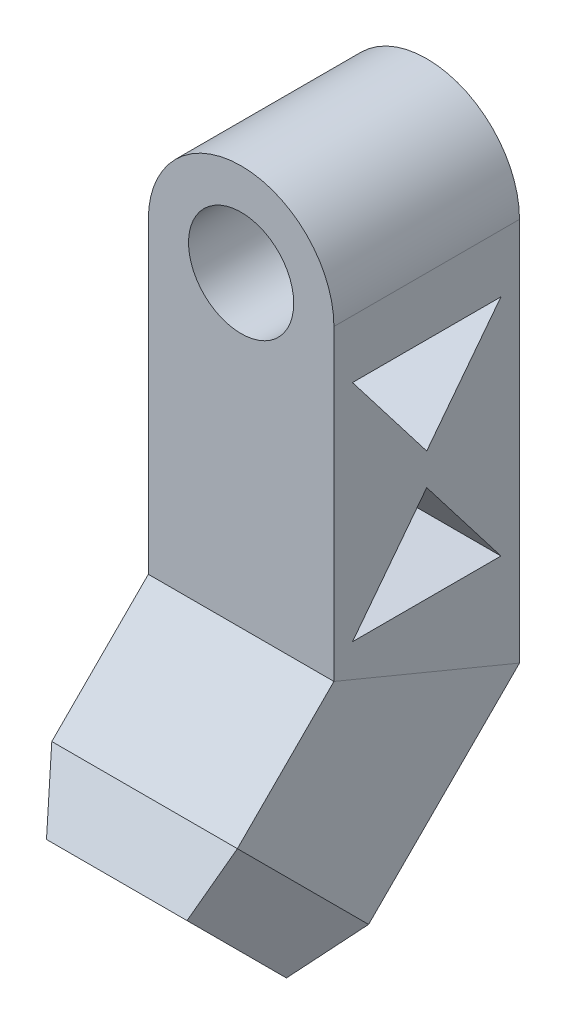
SolidWorks part; units mm, degrees
ref_plane "Front Plane" through (0, 0, 0) normal (0, 0, 1) x (1, 0, 0)
ref_plane "Top Plane" through (0, 0, 0) normal (0, 1, 0) x (1, 0, 0)
ref_plane "Right Plane" through (0, 0, 0) normal (1, 0, 0) x (0, 0, -1)
ref_plane "Plane2" through (0, 96.393, 0) normal (0, 1, 0) x (1, 0, 0)
sketch "Sketch10" plane through (0, 0, 0) normal (1, 0, 0) x (0, 0, -1)
  line L0 (0, 96.393) -> (0, 25.4)
  line L1 (55, 96.393) -> (-55, 96.393) construction
  line L2 (0, 25.4) -> (-25.4, 0)
  line L3 (55, 0) -> (-55, 0) construction
  dimension "D1" = 70.993
  dimension "D2" = 135
sketch "Sketch11" plane through (0, 96.393, 0) normal (0, 1, 0) x (1, 0, 0)
  line L1 (-19.05, -19.05) -> (19.05, -19.05)
  line L2 (-19.05, -19.05) -> (-19.05, 19.05)
  line L3 (-19.05, 19.05) -> (19.05, 19.05)
  line L4 (19.05, -19.05) -> (19.05, 19.05)
  line L5 (-19.05, -19.05) -> (19.05, 19.05) construction
  line L6 (-19.05, 19.05) -> (19.05, -19.05) construction
  point P0 (0, 0)
  dimension "D1" = 38.1
sweep "Sweep1" add profiles "Sketch11" path "Sketch10"
sketch "Sketch12" plane through (0, -12.7, 12.7) normal (0, -0.7071, 0.7071) x (1, 0, 0)
  line L8 (19.05, -1.0895) -> (19.05, 37.0105)
  line L9 (19.05, 37.0105) -> (-19.05, 37.0105)
  line L10 (-19.05, 37.0105) -> (-19.05, -1.0895)
  line L11 (-19.05, -1.0895) -> (19.05, -1.0895)
  line L12 (19.05, -1.0895) -> (19.05, 37.0105)
  line L13 (19.05, 37.0105) -> (-19.05, 37.0105)
  line L14 (-19.05, 37.0105) -> (-19.05, -1.0895)
  line L15 (-19.05, -1.0895) -> (19.05, -1.0895)
  dimension "D1" = 0
extrude "Boss-Extrude5" add sketch "Sketch12" along normal blind 12.7 draft 20
sketch "Sketch13" plane through (0, 0, -19.05) normal (0, 0, -1) x (-1, 0, 0)
  line L0 (55, 96.393) -> (-55, 96.393) construction
  line L1 (0, 55) -> (0, -55) construction
  line L2 (-19.05, 96.393) -> (19.05, 96.393)
  arc A0 (19.05, 96.393) -> (-19.05, 96.393) centre (0, 96.393) ccw
  dimension "D1" = 38.1
extrude "Boss-Extrude6" add sketch "Sketch13" against normal up to surface (38.1 mm away) up to face at (0, 64.8419, 19.05)
sketch "Sketch14" plane through (0, 0, 19.05) normal (0, 0, 1) x (1, 0, 0)
  circle A0 centre (0, 96.393) radius 10.795
  arc A1 (19.05, 96.393) -> (-19.05, 96.393) centre (0, 96.393) ccw construction
  dimension "D1" = 21.59
extrude "Cut-Extrude2" cut sketch "Sketch14" against normal blind 38.1
sketch "Sketch15" plane through (0, -21.6803, 21.6803) normal (0, -0.7071, 0.7071) x (1, 0, 0)
  line L0 (0, -34.9977) -> (0, 34.9977) construction
  line L4 (-14.4276, 32.3881) -> (-14.4276, 3.5329) construction
  line L5 (-14.4276, 3.5329) -> (14.4276, 3.5329) construction
  line L8 (0, 32.3881) -> (0, 3.5329) construction
  line L9 (14.4276, 32.3881) -> (-14.4276, 32.3881) construction
  circle A0 centre (0, 17.9605) radius 10.795
  point P12 (-14.4276, 17.9605)
  dimension "D1" = 21.59
extrude "Cut-Extrude3" cut sketch "Sketch15" against normal blind 12.7
sketch "Sketch16" plane through (-19.05, 0, 0) normal (-1, 0, 0) x (0, 0, 1)
  line L0 (-15.24, 38.4454) -> (0, 58.2328)
  line L2 (0, 58.2328) -> (15.24, 38.4454)
  line L3 (-19.05, 61.4842) -> (19.05, 61.4842) construction
  line L10 (-15.24, 38.4454) -> (15.24, 38.4454)
  line L13 (-19.05, 96.393) -> (-19.05, 17.5092) construction
  line L14 (19.05, 96.393) -> (19.05, 33.2908) construction
  line L15 (-15.24, 84.5229) -> (15.24, 84.5229)
  line L16 (0, 64.7355) -> (15.24, 84.5229)
  line L17 (-15.24, 84.5229) -> (0, 64.7355)
  dimension "D1" = 52.397
  dimension "D2" = 52.397
  dimension "D3" = 58.2328
  dimension "D4" = 38.4454
  dimension "D5" = 30.48
  dimension "D6" = 38.1
  dimension "D7" = 61.4842
  dimension "D9" = 38.4454
extrude "Cut-Extrude4" cut sketch "Sketch16" against normal blind 38.1
